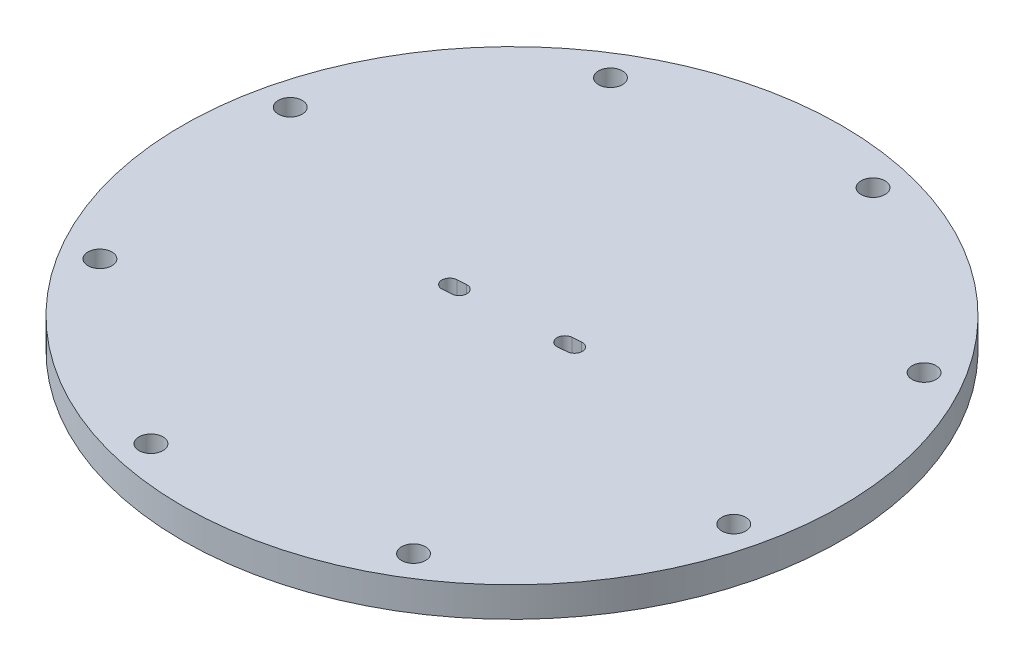
SolidWorks part; units mm, degrees
material "Aleación 6061"
ref_plane "Alzado" through (0, 0, 0) normal (0, 0, 1) x (1, 0, 0)
ref_plane "Planta" through (0, 0, 0) normal (0, 1, 0) x (1, 0, 0)
ref_plane "Vista lateral" through (0, 0, 0) normal (1, 0, 0) x (0, 0, -1)
sketch "Croquis1" plane through (0, 0, 0) normal (0, 1, 0) x (1, 0, 0)
  circle A0 centre (0, 0) radius 110
  dimension "D1" = 220
extrude "Saliente-Extruir1" add sketch "Croquis1" along normal blind 10
sketch "Croquis3" plane through (0, 10, 0) normal (0, 1, 0) x (1, 0, 0)
  line L0 (-19.4504, -1.39) -> (-16.458, -1.1762) construction
  line L1 (-19.6355, 1.2004) -> (-16.6431, 1.4143)
  line L2 (-19.2653, -3.9804) -> (-16.2729, -3.7666)
  line L3 (16.458, 1.1762) -> (19.4504, 1.4209) construction
  line L4 (16.2448, 3.7839) -> (19.2371, 4.0286)
  line L5 (16.6713, -1.4316) -> (19.6637, -1.1868)
  arc A2 (-19.6355, 1.2004) -> (-19.2653, -3.9804) centre (-19.4504, -1.39) ccw
  arc A3 (-16.2729, -3.7666) -> (-16.6431, 1.4143) centre (-16.458, -1.1762) ccw
  arc A4 (16.2448, 3.7839) -> (16.6713, -1.4316) centre (16.458, 1.1762) ccw
  arc A5 (19.6637, -1.1868) -> (19.2371, 4.0286) centre (19.4504, 1.4209) ccw
  point P2 (-17.9542, -1.2831)
  point P9 (17.9542, 1.2985)
extrude "Cortar-Extruir2" cut sketch "Croquis3" against normal through all
sketch "Croquis5" plane through (0, 10, 0) normal (0, 1, 0) x (1, 0, 0)
  circle A0 centre (-85.2097, -52.3385) radius 4
  circle A1 centre (-97.2612, 23.2434) radius 4
  circle A2 centre (-52.3385, 85.2097) radius 4
  circle A3 centre (23.2434, 97.2612) radius 4
  circle A4 centre (85.2097, 52.3385) radius 4
  circle A5 centre (97.2612, -23.2434) radius 4
  circle A6 centre (52.3385, -85.2097) radius 4
  circle A7 centre (-23.2434, -97.2612) radius 4
  point P20 (0, 0)
  dimension "D1" = 8
extrude "Cortar-Extruir3" cut sketch "Croquis5" against normal through all
